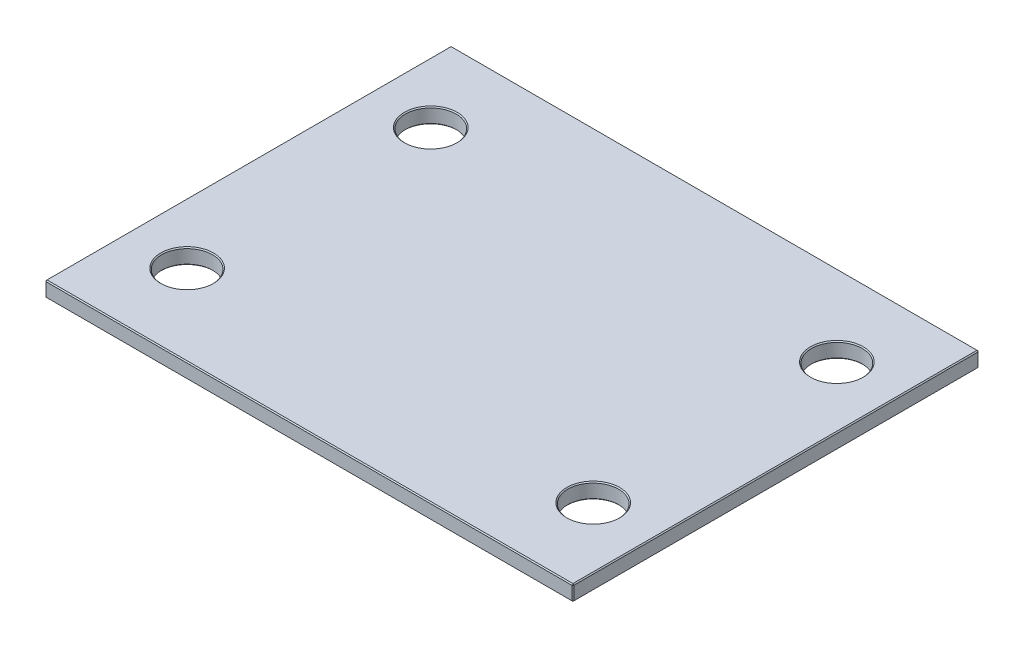
SolidWorks part; units mm, degrees
material "AISI 304"
ref_plane "Front Plane" through (0, 0, 0) normal (0, 0, 1) x (1, 0, 0)
ref_plane "Top Plane" through (0, 0, 0) normal (0, 1, 0) x (1, 0, 0)
ref_plane "Right Plane" through (0, 0, 0) normal (1, 0, 0) x (0, 0, -1)
sketch "Sketch1" plane through (0, 0, 0) normal (0, 1, 0) x (1, 0, 0)
  line L0 (-26, 12) -> (-20, 12) construction
  line L1 (-26, 20) -> (26, 20)
  line L2 (-26, 20) -> (-26, -20)
  line L3 (-26, -20) -> (26, -20)
  line L4 (26, 20) -> (26, -20)
  line L5 (-26, 20) -> (26, -20) construction
  line L6 (-26, -20) -> (26, 20) construction
  line L7 (-20, 12) -> (-20, 20) construction
  line L8 (26, 12) -> (20, 12) construction
  line L9 (20, 12) -> (20, 20) construction
  line L10 (-26, -12) -> (-20, -12) construction
  line L11 (-20, -12) -> (-20, -20) construction
  line L12 (20, -20) -> (20, -12) construction
  line L13 (20, -12) -> (26, -12) construction
  circle A0 centre (-20, 12) radius 2.5
  circle A1 centre (20, 12) radius 2.5
  circle A2 centre (20, -12) radius 2.5
  circle A3 centre (-20, -12) radius 2.5
  point P0 (0, 0)
  dimension "D5" = 5
  dimension "D1" = 40
  dimension "D2" = 52
  dimension "D3" = 6
  dimension "D4" = 8
extrude "Boss-Extrude1" add sketch "Sketch1" along normal blind 1.524
chamfer "Chamfer1" distance 0.1 angle 45 20 edges at (20, 0, 14.5) (20, 1.524, 14.5) (-20, 0, 14.5) (-20, 1.524, 14.5) (-20, 0, -9.5) (-20, 1.524, -9.5) (20, 0, -9.5) (20, 1.524, -9.5) (-26, 0, 0) (-26, 0.762, -20) (0, 0, -20) (26, 0.762, -20) (-26, 0.762, 20) (26, 0, 0) (0, 0, 20) (0, 1.524, 20) (26, 0.762, 20) (26, 1.524, 0) (0, 1.524, -20) (-26, 1.524, 0)
